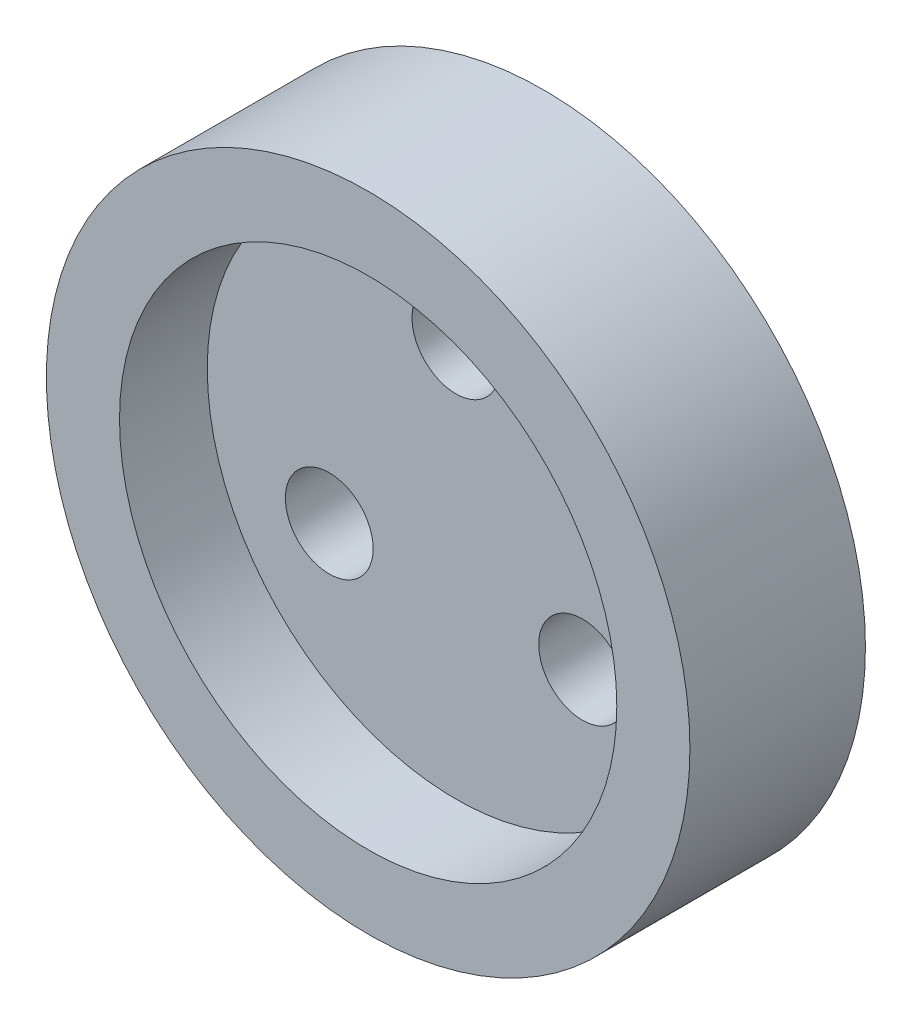
SolidWorks part; units mm, degrees
ref_plane "Front Plane" through (0, 0, 0) normal (0, 0, 1) x (1, 0, 0)
ref_plane "Top Plane" through (0, 0, 0) normal (0, 1, 0) x (1, 0, 0)
ref_plane "Right Plane" through (0, 0, 0) normal (1, 0, 0) x (0, 0, -1)
sketch "Esquisse1" plane through (0, 0, 0) normal (0, 0, 1) x (1, 0, 0)
  line L0 (0, 0) -> (0, 5) construction
  circle A0 centre (0, 0) radius 11
  circle A1 centre (0, 5) radius 1.5
  circle A4 centre (4.3301, -2.5) radius 1.5
  circle A5 centre (-4.3301, -2.5) radius 1.5
  point P11 (0, 0)
  dimension "D1" = 3
  dimension "D4" = 22
  dimension "D3" = 5
  dimension "D2" = 3
extrude "Boss.-Extru.1" add sketch "Esquisse1" along normal blind 3
sketch "Esquisse2" plane through (0, 0, 3) normal (0, 0, 1) x (1, 0, 0)
  circle A0 centre (0, 0) radius 8.5
  circle A1 centre (0, 0) radius 11
  circle A2 centre (0, 0) radius 11 construction
  dimension "D1" = 17
extrude "Boss.-Extru.2" add sketch "Esquisse2" along normal blind 3
